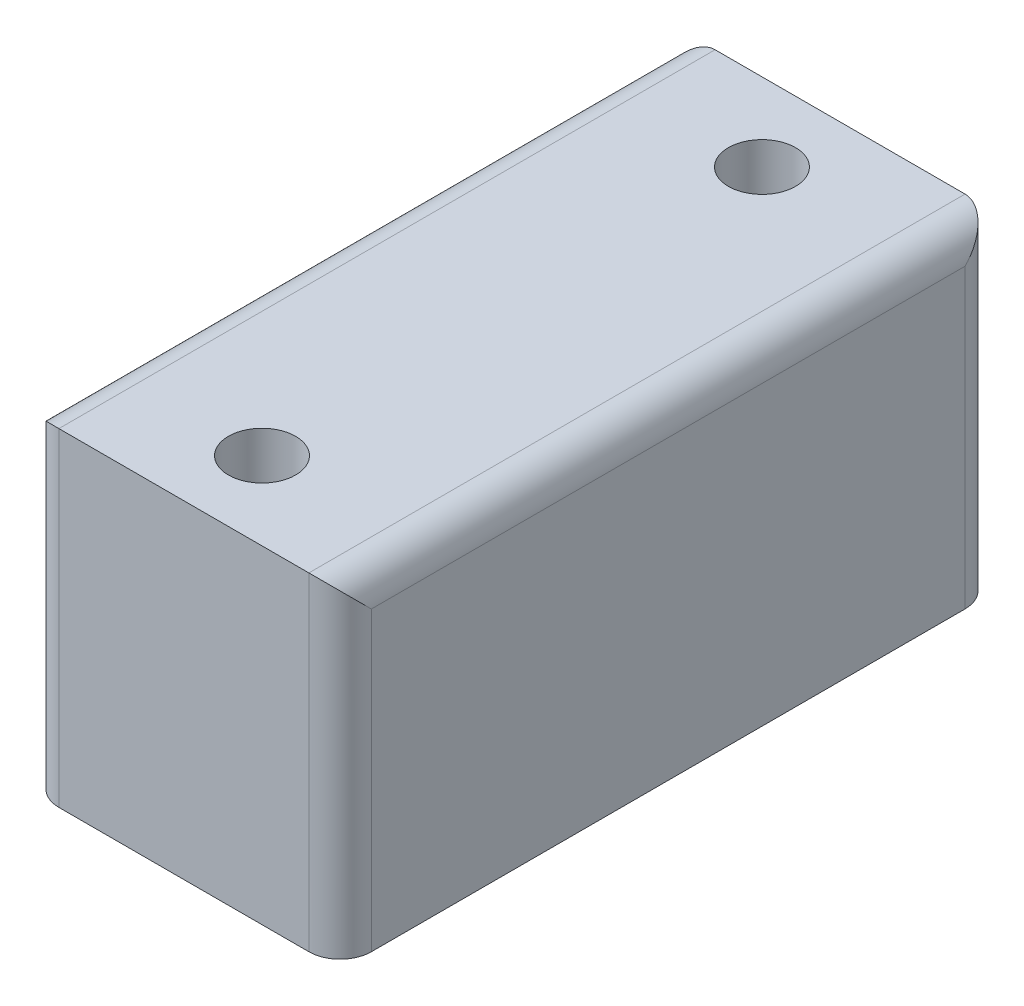
SolidWorks part; units mm, degrees
ref_plane "前视基准面" through (0, 0, 0) normal (0, 0, 1) x (1, 0, 0)
ref_plane "上视基准面" through (0, 0, 0) normal (0, 1, 0) x (1, 0, 0)
ref_plane "右视基准面" through (0, 0, 0) normal (1, 0, 0) x (0, 0, -1)
other "Configuration Table"
sketch "草图1" plane through (0, 0, 0) normal (0, 0, 1) x (1, 0, 0)
  line L1 (0, 0) -> (-20, 0)
  line L2 (0, 0) -> (0, 21)
  line L3 (0, 21) -> (-20, 21)
  line L4 (-20, 0) -> (-20, 21)
  dimension "D1" = 21
  dimension "D2" = 20
extrude "凸台-拉伸1" add sketch "草图1" along normal blind 42
sketch "草图2" plane through (0, 21, 0) normal (0, 1, 0) x (1, 0, 0)
  line L0 (0, -21) -> (-20, -21) construction
  line L1 (0, -42) -> (0, 0) construction
  line L2 (-20, -42) -> (-20, 0) construction
  line L3 (-10, 0) -> (-10, -42) construction
  line L4 (0, 0) -> (-20, 0) construction
  line L5 (0, -42) -> (-20, -42) construction
  circle A0 centre (-10, -5) radius 2.15
  circle A1 centre (-10, -37) radius 2.15
  dimension "D1" = 32
  dimension "D2" = 4.3
extrude "切除-拉伸1" cut sketch "草图2" against normal up to next
fillet "圆角1" radius 2 6 edges at (-20, 10.5, 0) (0, 10.5, 0) (-20, 10.5, 42) (0, 10.5, 42) (0, 21, 21) (-20, 21, 21)
